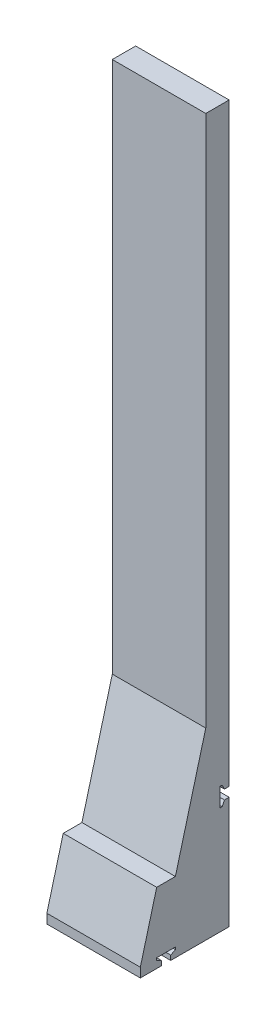
SolidWorks part; units mm, degrees
ref_plane "前视基准面" through (0, 0, 0) normal (0, 0, 1) x (1, 0, 0)
ref_plane "上视基准面" through (0, 0, 0) normal (0, 1, 0) x (1, 0, 0)
ref_plane "右视基准面" through (0, 0, 0) normal (1, 0, 0) x (0, 0, -1)
other "Configuration Table"
sketch "草图1" plane through (1150, 0, 0) normal (1, 0, 0) x (0, 0, -1)
  line L1 (-200, 50) -> (-200, 60)
  line L2 (-200, 60) -> (-182.5, 125.3109)
  line L3 (-182.5, 125.3109) -> (-162.5, 125.3109)
  line L4 (-162.5, 125.3109) -> (-130, 246.6025)
  line L5 (-130, 246.6025) -> (-130, 816.1392)
  line L6 (-130, 816.1392) -> (-105, 816.1392)
  line L7 (-105, 816.1392) -> (-105, 180)
  line L8 (-105, 180) -> (-110, 180)
  line L9 (-110, 180) -> (-112.5, 185)
  line L10 (-112.5, 185) -> (-115, 185)
  line L11 (-115, 185) -> (-115, 165)
  line L12 (-115, 165) -> (-112.5, 165)
  line L13 (-112.5, 165) -> (-110, 170)
  line L14 (-110, 170) -> (-105, 170)
  line L15 (-105, 170) -> (-105, 50)
  line L16 (-105, 50) -> (-167.5, 50)
  line L17 (-167.5, 50) -> (-167.5, 55)
  line L18 (-167.5, 55) -> (-162.5, 57.5)
  line L19 (-162.5, 57.5) -> (-162.5, 60)
  line L20 (-162.5, 60) -> (-182.5, 60)
  line L21 (-182.5, 60) -> (-182.5, 57.5)
  line L22 (-182.5, 57.5) -> (-177.5, 55)
  line L23 (-177.5, 55) -> (-177.5, 50)
  line L24 (-177.5, 50) -> (-200, 50)
  point P0 (0, 0)
  dimension "D1" = 40
  dimension "D2" = 10
  dimension "D3" = 75
  dimension "D4" = 25
extrude "凸台-拉伸1" add sketch "草图1" along normal blind 100
